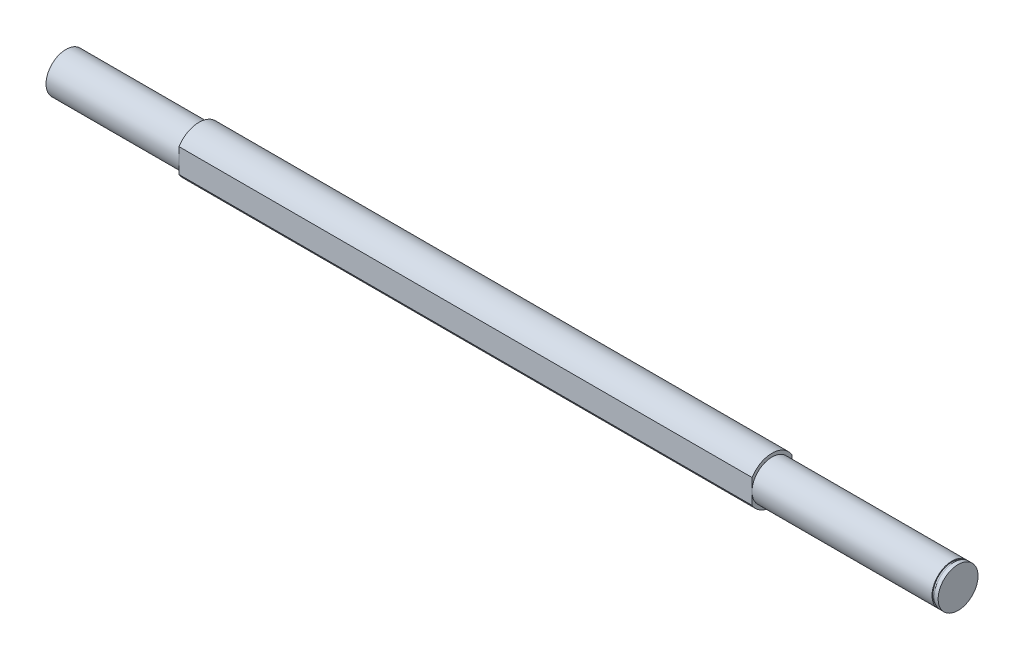
SolidWorks part; units mm, degrees
ref_plane "Ön Düzlem" through (0, 0, 0) normal (0, 0, 1) x (1, 0, 0)
ref_plane "Üst Düzlem" through (0, 0, 0) normal (0, 1, 0) x (1, 0, 0)
ref_plane "Sağ Düzlem" through (0, 0, 0) normal (1, 0, 0) x (0, 0, -1)
sketch "Sketch1" plane through (0, 0, 0) normal (0, 0, 1) x (1, 0, 0)
  line L0 (-335.5, 0) -> (335.5, 0)
  line L1 (-335.5, 0) -> (-335.5, 15)
  line L2 (-335.5, 15) -> (-235.5, 15)
  line L3 (-235.5, 15) -> (-235.5, 17.5)
  line L4 (-235.5, 17.5) -> (195.5, 17.5)
  line L5 (195.5, 17.5) -> (195.5, 15)
  line L6 (195.5, 15) -> (335.5, 15)
  line L7 (335.5, 15) -> (335.5, 0)
  point P4 (0, 0)
  dimension "D1" = 140
  dimension "D2" = 431
  dimension "D3" = 100
  dimension "D4" = 15
  dimension "D5" = 17.5
revolve "Revolve1" add sketch "Sketch1" angle 360 about L0
sketch "Sketch2" plane through (-235.5, 0, 0) normal (-1, 0, 0) x (0, 0, 1)
  line L0 (-14.9366, 9.1186) -> (-15.0627, -8.9088)
  line L1 (0, 0) -> (0, 5.213) construction
  line L2 (14.9366, 9.1186) -> (15.0627, -8.9088)
  circle A0 centre (0, 0) radius 15 construction
  circle A2 centre (0, 0) radius 17.5 construction
  arc A4 (-14.9366, 9.1186) -> (-15.0627, -8.9088) centre (0, 0) ccw
  arc A5 (14.9366, 9.1186) -> (15.0627, -8.9088) centre (0, 0) cw
extrude "Cut-Extrude1" cut sketch "Sketch2" against normal up to surface (431 mm away) up to face at (195.5, 0, 17.5)
sketch "Sketch3" plane through (0, 0, 0) normal (0, 1, 0) x (1, 0, 0)
  line L0 (335.5, 15) -> (195.5, 15) construction
  line L1 (330.9, 15) -> (332.5, 15)
  line L2 (330.9, 15) -> (330.9, 14.3)
  line L3 (330.9, 14.3) -> (332.5, 14.3)
  line L4 (332.5, 15) -> (332.5, 14.3)
  line L5 (335.5, 0) -> (323.6626, 0) construction
  line L6 (335.5, -15) -> (335.5, 15) construction
  point P11 (331.7, 14.3)
  dimension "D1" = 1.6
  dimension "D2" = 14.3
  dimension "D3" = 3
revolve "Cut-Revolve1" cut sketch "Sketch3" angle 360 about L5
sketch "Sketch5" plane through (335.5, 0, 0) normal (1, 0, 0) x (0, 0, -1)
  line L0 (0, 0) -> (0, 163.2156) construction
  line L1 (0, 163.2156) -> (17.1227, -22.3084) construction
  arc A0 (14.9996, 0.1049) -> (-14.9996, 0.1049) centre (0, 0) ccw construction
  point P3 (0, 45.0665)
  dimension "D1" = 5.273
ref_plane "Plane2" through (0, 1.3785, -14.9365) normal (0, -0.0919, 0.9958) x (0, -0.9958, -0.0919)
sketch "Sketch6" plane through (0, 1.3785, -14.9365) normal (0, -0.0919, 0.9958) x (0, -0.9958, -0.0919)
  line L0 (0, 322.5) -> (0, 292.5) construction
  line L1 (5, 322.5) -> (5, 292.5)
  line L2 (-5, 322.5) -> (-5, 292.5)
  line L3 (15, 335.5) -> (-15, 335.5) construction
  arc A0 (5, 322.5) -> (-5, 322.5) centre (0, 322.5) ccw
  arc A1 (-5, 292.5) -> (5, 292.5) centre (0, 292.5) ccw
  point P3 (0, 307.5)
  point P8 (0, 327.5)
  point P9 (0, 287.5)
  point P12 (10.4986, 357.2334)
  dimension "D1" = 10
  dimension "D2" = 40
  dimension "D3" = 8
extrude "Cut-Extrude2" cut sketch "Sketch6" along normal blind 5
